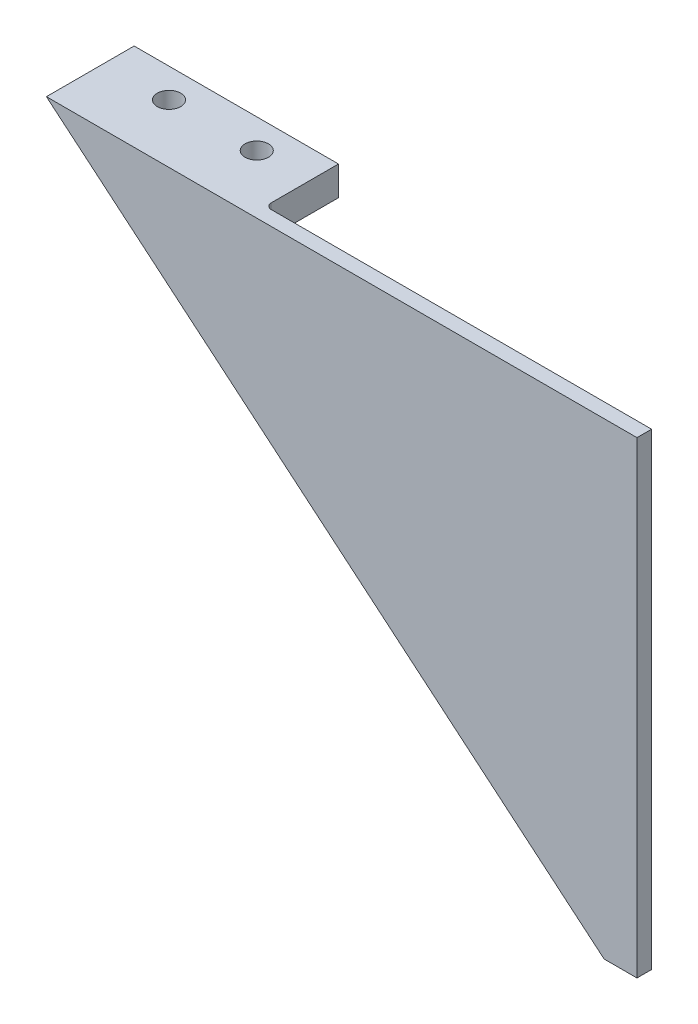
SolidWorks part; units mm, degrees
ref_plane "前视基准面" through (0, 0, 0) normal (0, 0, 1) x (1, 0, 0)
ref_plane "上视基准面" through (0, 0, 0) normal (0, 1, 0) x (1, 0, 0)
ref_plane "右视基准面" through (0, 0, 0) normal (1, 0, 0) x (0, 0, -1)
sketch "草图2" plane through (0, 0, 0) normal (0, 0, 1) x (1, 0, 0)
  line L1 (-140, 75) -> (140, 75)
  line L2 (-140, 75) -> (-140, -75)
  line L3 (-140, -75) -> (140, -75)
  line L4 (140, 75) -> (140, -75)
  line L5 (0, -75) -> (0, 75) construction
  line L6 (-140, 0) -> (140, 0) construction
  point P0 (0, 0)
  dimension "D1" = 150
  dimension "D2" = 280
extrude "凸台-拉伸1" add sketch "草图2" along normal blind 5
sketch "草图3" plane through (0, 75, 0) normal (0, 1, 0) x (1, 0, 0)
  line L6 (-140, 0) -> (140, 0)
  line L7 (-140, 0) -> (-140, 25)
  line L8 (-140, 25) -> (140, 25)
  line L9 (140, 0) -> (140, 25)
  dimension "D2" = 25
extrude "凸台-拉伸2" add sketch "草图3" against normal blind 10
sketch "草图4" plane through (0, 0, 0) normal (0, 0, -1) x (-1, 0, 0)
  line L0 (75.4621, 103.1472) -> (-172.0079, -104.5047)
  line L1 (-140, 65) -> (140, 65) construction
  line L2 (140, 65) -> (-140, 65) construction
  line L3 (-172.0079, -104.5047) -> (179.3283, -108.5214)
  line L4 (179.3283, -108.5214) -> (159.9982, 98.6463)
  line L5 (159.9982, 98.6463) -> (75.4621, 103.1472)
  point P4 (30, 65)
  dimension "D1" = 40
  dimension "D2" = 110
extrude "切除-拉伸1" cut sketch "草图4" against normal mid plane 50 contours L5 L0 L3 L4
sketch "草图5" plane through (0, 65, 0) normal (0, -1, 0) x (1, 0, 0)
  line L0 (-30, -25) -> (-30, 0) construction
  line L1 (136.8455, 0) -> (-30, 0) construction
  circle A0 centre (-20, -15) radius 4
  circle A1 centre (10, -15) radius 4
  point P6 (-13.6847, -15.1191)
  point P7 (-19.2816, -17.8493)
  dimension "D1" = 8
  dimension "D3" = 10
  dimension "D2" = 30
  dimension "D4" = 15
extrude "切除-拉伸2" cut sketch "草图5" against normal blind 50
sketch "草图6" plane through (140, 0, 0) normal (1, 0, 0) x (0, 0, -1)
  line L1 (-5, 75) -> (0, 75)
  line L2 (-5, 75) -> (-5, -85)
  line L3 (-5, -85) -> (0, -85)
  line L4 (0, 75) -> (0, -85)
  dimension "D1" = 160
extrude "凸台-拉伸3" add sketch "草图6" along normal blind 20
sketch "草图7" plane through (0, 0, 5) normal (0, 0, 1) x (1, 0, 0)
  line L0 (136.8455, -75) -> (140, -77.6469)
  line L1 (140, -75) -> (140, -85) construction
  line L2 (140, -77.6469) -> (140, -75)
  line L3 (140, -75) -> (136.8455, -75)
  line L4 (136.8455, -75) -> (-41.9175, 75) construction
extrude "凸台-拉伸4" add sketch "草图7" against normal up to surface (5 mm away) up to face at (123.3557, -5, 0)
sketch "草图8" plane through (0, 0, 5) normal (0, 0, 1) x (1, 0, 0)
  line L0 (140, -77.6469) -> (153.8568, -89.2742)
  line L1 (153.8568, -89.2742) -> (129.7195, -89.8988)
  line L2 (129.7195, -89.8988) -> (140, -77.6469)
  line L3 (140, -77.6469) -> (-41.9175, 75) construction
extrude "切除-拉伸3" cut sketch "草图8" against normal blind 20
sketch "草图9" plane through (0, 65, 0) normal (0, -1, 0) x (1, 0, 0)
  line L0 (-30, 0) -> (140, 0) construction
  line L1 (27.95, 0) -> (140, 0)
  line L2 (27.95, 0) -> (27.95, -25)
  line L3 (27.95, -25) -> (140, -25)
  line L4 (140, 0) -> (140, -25)
  dimension "D1" = 112.05
extrude "切除-拉伸4" cut sketch "草图9" against normal blind 20
fillet "圆角1" radius 2 2 edges at (27.95, 70, 0) (-1.025, 65, 0)
